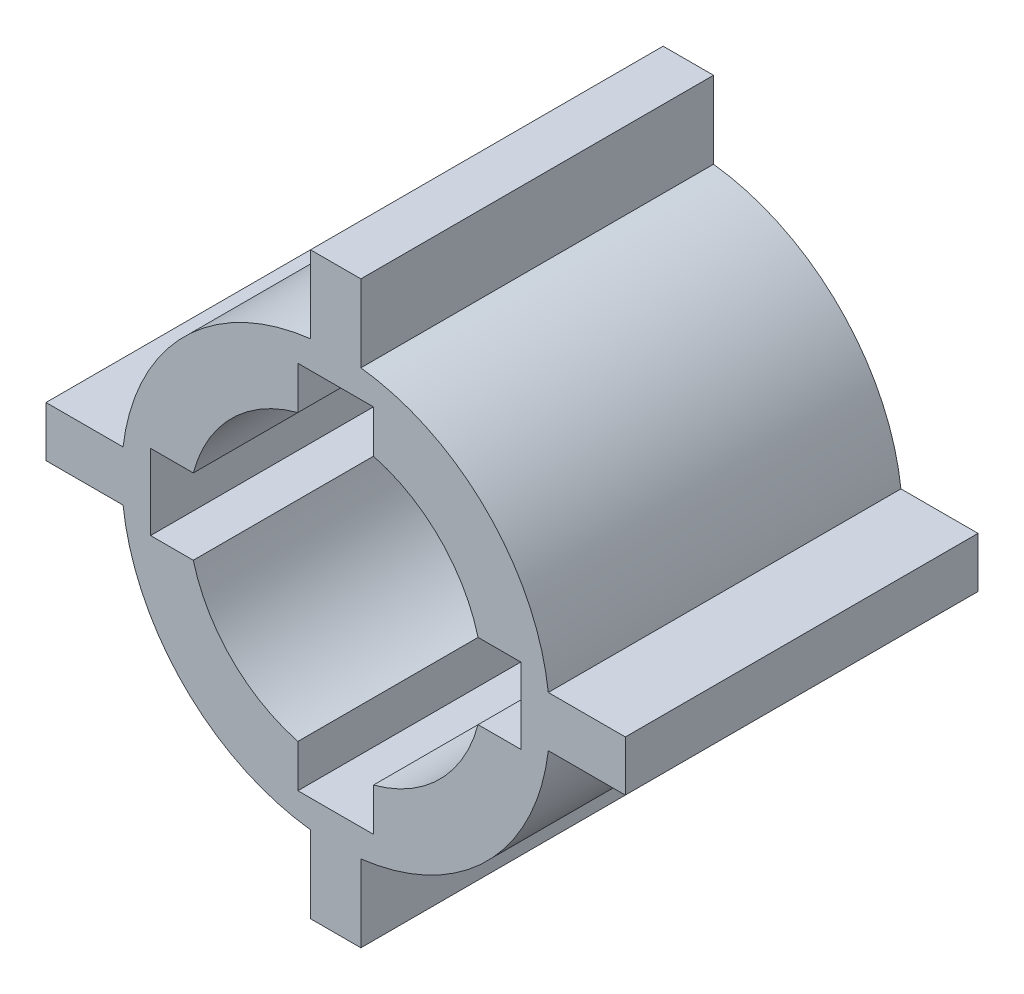
SolidWorks part; units mm, degrees
ref_plane "Front Plane" through (0, 0, 0) normal (0, 0, 1) x (1, 0, 0)
ref_plane "Top Plane" through (0, 0, 0) normal (0, 1, 0) x (1, 0, 0)
ref_plane "Right Plane" through (0, 0, 0) normal (1, 0, 0) x (0, 0, -1)
sketch "Sketch1" plane through (0, 0, 0) normal (0, 0, 1) x (1, 0, 0)
  line L0 (-1.5, 5.6528) -> (-1.5, 7.3485)
  line L1 (-1.5, 4.3485) -> (1.5, 4.3485) construction
  line L2 (-1.5, 4.3485) -> (-1.5, 7.3485) construction
  line L3 (-1.5, 7.3485) -> (1.5, 7.3485) construction
  line L4 (1.5, 4.3485) -> (1.5, 7.3485) construction
  line L5 (-1.5, 4.3485) -> (1.5, 7.3485) construction
  line L6 (-1.5, 7.3485) -> (1.5, 4.3485) construction
  line L7 (4.3485, -1.5) -> (7.3485, -1.5) construction
  line L8 (4.3485, -1.5) -> (4.3485, 1.5) construction
  line L9 (4.3485, 1.5) -> (7.3485, 1.5) construction
  line L10 (7.3485, -1.5) -> (7.3485, 1.5) construction
  line L11 (4.3485, -1.5) -> (7.3485, 1.5) construction
  line L12 (4.3485, 1.5) -> (7.3485, -1.5) construction
  line L13 (-1.5, -7.3485) -> (1.5, -7.3485) construction
  line L14 (-1.5, -7.3485) -> (-1.5, -4.3485) construction
  line L15 (-1.5, -4.3485) -> (1.5, -4.3485) construction
  line L16 (1.5, -7.3485) -> (1.5, -4.3485) construction
  line L17 (-1.5, -7.3485) -> (1.5, -4.3485) construction
  line L18 (-1.5, -4.3485) -> (1.5, -7.3485) construction
  line L19 (-7.3485, -1.5) -> (-4.3485, -1.5) construction
  line L20 (-7.3485, -1.5) -> (-7.3485, 1.5) construction
  line L21 (-7.3485, 1.5) -> (-4.3485, 1.5) construction
  line L22 (-4.3485, -1.5) -> (-4.3485, 1.5) construction
  line L23 (-7.3485, -1.5) -> (-4.3485, 1.5) construction
  line L24 (-7.3485, 1.5) -> (-4.3485, -1.5) construction
  line L25 (-1.5, 7.3485) -> (1.5, 7.3485)
  line L26 (1.5, 7.3485) -> (1.5, 5.6528)
  line L27 (-5.6528, -1.5) -> (-7.3485, -1.5)
  line L28 (-7.3485, -1.5) -> (-7.3485, 1.5)
  line L29 (-7.3485, 1.5) -> (-5.6528, 1.5)
  line L30 (1.5, -5.6528) -> (1.5, -7.3485)
  line L31 (1.5, -7.3485) -> (-1.5, -7.3485)
  line L32 (-1.5, -7.3485) -> (-1.5, -5.6528)
  line L33 (5.6528, 1.5) -> (7.3485, 1.5)
  line L34 (7.3485, 1.5) -> (7.3485, -1.5)
  line L35 (7.3485, -1.5) -> (5.6528, -1.5)
  line L36 (-1, 8.441) -> (-1, 11.5)
  line L37 (-1, 5.5) -> (1, 5.5) construction
  line L38 (-1, 5.5) -> (-1, 11.5) construction
  line L39 (-1, 11.5) -> (1, 11.5) construction
  line L40 (1, 5.5) -> (1, 11.5) construction
  line L41 (-1, 5.5) -> (1, 11.5) construction
  line L42 (-1, 11.5) -> (1, 5.5) construction
  line L43 (5.5, -1) -> (11.5, -1) construction
  line L44 (5.5, -1) -> (5.5, 1) construction
  line L45 (5.5, 1) -> (11.5, 1) construction
  line L46 (11.5, -1) -> (11.5, 1) construction
  line L47 (5.5, -1) -> (11.5, 1) construction
  line L48 (5.5, 1) -> (11.5, -1) construction
  line L49 (-1, -11.5) -> (1, -11.5) construction
  line L50 (-1, -11.5) -> (-1, -5.5) construction
  line L51 (-1, -5.5) -> (1, -5.5) construction
  line L52 (1, -11.5) -> (1, -5.5) construction
  line L53 (-1, -11.5) -> (1, -5.5) construction
  line L54 (-1, -5.5) -> (1, -11.5) construction
  line L55 (-11.5, -1) -> (-5.5, -1) construction
  line L56 (-11.5, -1) -> (-11.5, 1) construction
  line L57 (-11.5, 1) -> (-5.5, 1) construction
  line L58 (-5.5, -1) -> (-5.5, 1) construction
  line L59 (-11.5, -1) -> (-5.5, 1) construction
  line L60 (-11.5, 1) -> (-5.5, -1) construction
  line L61 (-1, 11.5) -> (1, 11.5)
  line L62 (1, 11.5) -> (1, 8.441)
  line L63 (-8.441, -1) -> (-11.5, -1)
  line L64 (-11.5, -1) -> (-11.5, 1)
  line L65 (-11.5, 1) -> (-8.441, 1)
  line L66 (-1, -8.441) -> (-1, -11.5)
  line L67 (-1, -11.5) -> (1, -11.5)
  line L68 (1, -11.5) -> (1, -8.441)
  line L69 (8.441, -1) -> (11.5, -1)
  line L70 (11.5, -1) -> (11.5, 1)
  line L71 (11.5, 1) -> (8.441, 1)
  arc A0 (-1.5, 5.6528) -> (-5.6528, 1.5) centre (0, 0) ccw
  circle A1 centre (0, 0) radius 7.5 construction
  arc A2 (5.6528, 1.5) -> (1.5, 5.6528) centre (0, 0) ccw
  arc A3 (1.5, -5.6528) -> (5.6528, -1.5) centre (0, 0) ccw
  arc A4 (-5.6528, -1.5) -> (-1.5, -5.6528) centre (0, 0) ccw
  arc A5 (-8.441, -1) -> (-1, -8.441) centre (0, 0) ccw
  arc A6 (-1, 8.441) -> (-8.441, 1) centre (0, 0) ccw
  arc A7 (8.441, 1) -> (1, 8.441) centre (0, 0) ccw
  arc A8 (1, -8.441) -> (8.441, -1) centre (0, 0) ccw
  point P4 (0, 5.8485)
  point P9 (5.8485, 0)
  point P14 (0, -5.8485)
  point P19 (-5.8485, 0)
  point P28 (0, 8.5)
  point P37 (8.5, 0)
  point P42 (0, -8.5)
  point P47 (-8.5, 0)
  dimension "D1" = 15
  dimension "D3" = 17
  dimension "D2" = 3
  dimension "D4" = 2
  dimension "D5" = 6
extrude "Boss-Extrude1" add sketch "Sketch1" along normal blind 14
